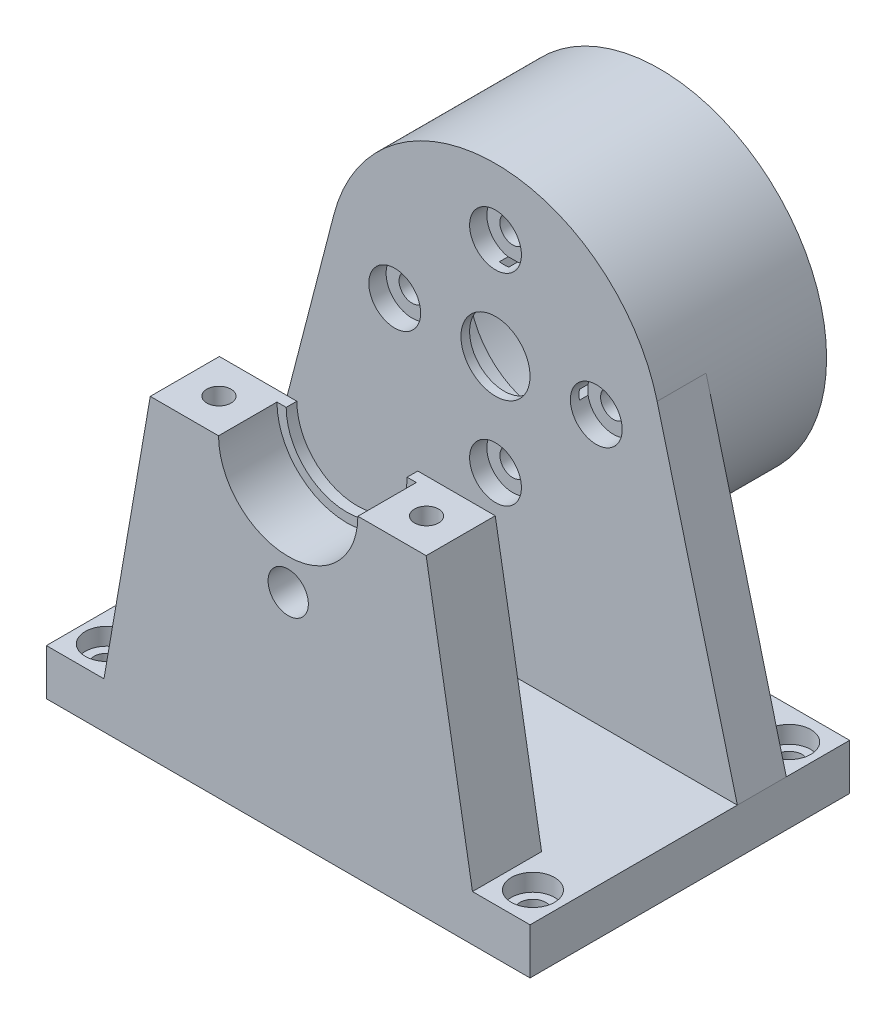
SolidWorks part; units mm, degrees
material "PET"
ref_plane "Piano frontale" through (0, 0, 0) normal (0, 0, 1) x (1, 0, 0)
ref_plane "Piano superiore" through (0, 0, 0) normal (0, 1, 0) x (1, 0, 0)
ref_plane "Piano destro" through (0, 0, 0) normal (1, 0, 0) x (0, 0, -1)
sketch "Schizzo1" plane through (0, 0, 0) normal (0, 0, 1) x (1, 0, 0)
  line L0 (-42, -54.5) -> (42, -54.5)
  line L1 (21, -17.1) -> (-21, -17.1)
  line L2 (21, -17.1) -> (21, 17.1)
  line L3 (21, 17.1) -> (-21, 17.1)
  line L4 (-21, -17.1) -> (-21, 17.1)
  line L5 (21, -17.1) -> (-21, 17.1) construction
  line L6 (21, 17.1) -> (-21, -17.1) construction
  line L7 (-42, -54.5) -> (-42, -46.5)
  line L8 (-42, -46.5) -> (-32, -46.5)
  line L9 (-32, -46.5) -> (-21, 17.1)
  line L10 (42, -54.5) -> (42, -46.5)
  line L11 (42, -46.5) -> (32, -46.5)
  line L12 (32, -46.5) -> (21, 17.1)
  line L13 (-23.9575, 0) -> (23.9575, 0)
  circle A0 centre (0, 0) radius 12.1
  point P9 (0, -54.5)
  dimension "D1" = 24.2
  dimension "D2" = 42
  dimension "D3" = 17.1
  dimension "D4" = 54.5
  dimension "D5" = 84
  dimension "D6" = 8
  dimension "D7" = 10
extrude "Estrusione-Estrusione1" add sketch "Schizzo1" along normal blind 12 contours A0 L13 L4 L1 L2 | L13 L9 L8 L7 L0 L10 L11 L12 L2 L1 L4
sketch "Schizzo2" plane through (0, 0, 12) normal (0, 0, 1) x (1, 0, 0)
  line L0 (-12.1, 0) -> (12.1, 0)
  circle A0 centre (0, 0) radius 10.5
  arc A1 (-12.1, 0) -> (12.1, 0) centre (0, 0) ccw construction
  arc A2 (-12.1, 0) -> (12.1, 0) centre (0, 0) ccw
  arc M11 (12.1, 0) -> (-12.1, 0) centre (0, 0) cw
  dimension "D1" = 21
extrude "Estrusione-Estrusione2" add sketch "Schizzo2" against normal blind 1.85 contours A0 L0 M11
sketch "Schizzo3" plane through (0, 0, 0) normal (0, 0, -1) x (-1, 0, 0)
  line L0 (-12.1, 0) -> (12.1, 0)
  circle A0 centre (0, 0) radius 10.5
  arc A1 (-12.1, 0) -> (12.1, 0) centre (0, 0) ccw construction
  arc A2 (-12.1, 0) -> (12.1, 0) centre (0, 0) ccw
  arc M3 (12.1, 0) -> (-12.1, 0) centre (0, 0) cw
  dimension "D1" = 21
extrude "Estrusione-Estrusione3" add sketch "Schizzo3" against normal blind 1.85 contours A0 L0 M3
sketch "Schizzo4" plane through (0, 0, 0) normal (0, 0, -1) x (-1, 0, 0)
  line L0 (-32, -46.5) -> (32, -46.5)
  line L9 (23.9575, 0) -> (10.5, 0)
  line L10 (-10.5, 0) -> (-23.9575, 0)
  line L11 (-23.9575, 0) -> (-32, -46.5)
  line L12 (-32, -46.5) -> (-42, -46.5)
  line L13 (-42, -46.5) -> (-42, -54.5)
  line L14 (-42, -54.5) -> (42, -54.5)
  line L15 (42, -54.5) -> (42, -46.5)
  line L16 (42, -46.5) -> (32, -46.5)
  line L17 (32, -46.5) -> (23.9575, 0)
  line L18 (23.9575, 0) -> (10.5, 0)
  line L19 (-10.5, 0) -> (-23.9575, 0)
  line L20 (-23.9575, 0) -> (-32, -46.5)
  line L21 (-32, -46.5) -> (-42, -46.5)
  line L22 (-42, -46.5) -> (-42, -54.5)
  line L23 (-42, -54.5) -> (42, -54.5)
  line L24 (42, -54.5) -> (42, -46.5)
  line L25 (42, -46.5) -> (32, -46.5)
  line L26 (32, -46.5) -> (23.9575, 0)
  circle A0 centre (0, 0) radius 54
  arc A1 (-10.5, 0) -> (10.5, 0) centre (0, 0) ccw
  arc A2 (-10.5, 0) -> (10.5, 0) centre (0, 0) ccw
  line M15 (-32, -46.5) -> (-42, -46.5)
  line M16 (-42, -46.5) -> (-42, -54.5)
  line M17 (-42, -54.5) -> (42, -54.5)
  line M18 (42, -54.5) -> (42, -46.5)
  line M19 (42, -46.5) -> (32, -46.5)
  dimension "D2" = 108
  dimension "D1" = 0
extrude "Estrusione-Estrusione4" add sketch "Schizzo4" along normal blind 23.5 contours A0 L0 M15 M16 M17 M18 M19
sketch "Schizzo5" plane through (0, 0, -23.5) normal (0, 0, -1) x (-1, 0, 0)
  line L9 (23.9575, 0) -> (10.5, 0)
  line L10 (32, -46.5) -> (23.9575, 0)
  line L11 (42, -46.5) -> (32, -46.5)
  line L12 (42, -54.5) -> (42, -46.5)
  line L13 (-42, -54.5) -> (42, -54.5)
  line L14 (-42, -46.5) -> (-42, -54.5)
  line L15 (-32, -46.5) -> (-42, -46.5)
  line L16 (-23.9575, 0) -> (-32, -46.5)
  line L17 (-10.5, 0) -> (-23.9575, 0)
  line L18 (23.9575, 0) -> (10.5, 0)
  line L19 (32, -46.5) -> (23.9575, 0)
  line L20 (42, -46.5) -> (32, -46.5)
  line L21 (42, -54.5) -> (42, -46.5)
  line L22 (-42, -54.5) -> (42, -54.5)
  line L23 (-42, -46.5) -> (-42, -54.5)
  line L24 (-32, -46.5) -> (-42, -46.5)
  line L25 (-23.9575, 0) -> (-32, -46.5)
  line L26 (-10.5, 0) -> (-23.9575, 0)
  arc A1 (-10.5, 0) -> (10.5, 0) centre (0, 0) ccw
  arc A2 (-10.5, 0) -> (10.5, 0) centre (0, 0) ccw
  dimension "D1" = 0
extrude "Estrusione-Estrusione5" add sketch "Schizzo5" along normal blind 1.85
sketch "Schizzo6" plane through (0, 0, -25.35) normal (0, 0, -1) x (-1, 0, 0)
  line L2 (-10.5, 0) -> (-12.1, 0)
  line L3 (12.1, 0) -> (10.5, 0)
  line L4 (-10.5, 0) -> (-12.1, 0)
  line L5 (12.1, 0) -> (10.5, 0)
  line L13 (-10.5, 0) -> (-23.9575, 0)
  line L14 (-23.9575, 0) -> (-32, -46.5)
  line L15 (-32, -46.5) -> (-42, -46.5)
  line L16 (-42, -46.5) -> (-42, -54.5)
  line L17 (-42, -54.5) -> (42, -54.5)
  line L18 (42, -54.5) -> (42, -46.5)
  line L19 (42, -46.5) -> (32, -46.5)
  line L20 (32, -46.5) -> (23.9575, 0)
  line L21 (23.9575, 0) -> (10.5, 0)
  line L22 (-10.5, 0) -> (-23.9575, 0)
  line L23 (-23.9575, 0) -> (-32, -46.5)
  line L24 (-32, -46.5) -> (-42, -46.5)
  line L25 (-42, -46.5) -> (-42, -54.5)
  line L26 (-42, -54.5) -> (42, -54.5)
  line L27 (42, -54.5) -> (42, -46.5)
  line L28 (42, -46.5) -> (32, -46.5)
  line L29 (32, -46.5) -> (23.9575, 0)
  line L30 (23.9575, 0) -> (10.5, 0)
  arc A1 (-10.5, 0) -> (10.5, 0) centre (0, 0) ccw
  arc A2 (-10.5, 0) -> (10.5, 0) centre (0, 0) ccw
  arc A3 (-12.1, 0) -> (12.1, 0) centre (0, 0) ccw
  arc A4 (-10.5, 0) -> (10.5, 0) centre (0, 0) ccw
  arc A5 (-12.1, 0) -> (12.1, 0) centre (0, 0) ccw
  arc A6 (-10.5, 0) -> (10.5, 0) centre (0, 0) ccw
  line M16 (-10.5, 0) -> (-23.9575, 0)
  line M17 (-23.9575, 0) -> (-32, -46.5)
  line M18 (-32, -46.5) -> (-42, -46.5)
  line M19 (-42, -46.5) -> (-42, -54.5)
  line M20 (-42, -54.5) -> (42, -54.5)
  line M21 (42, -54.5) -> (42, -46.5)
  line M22 (42, -46.5) -> (32, -46.5)
  line M23 (32, -46.5) -> (23.9575, 0)
  line M24 (23.9575, 0) -> (10.5, 0)
  dimension "D1" = 0
  dimension "D2" = 0
extrude "Estrusione-Estrusione6" add sketch "Schizzo6" along normal blind 8.3 contours A5 M16 M17 M18 M19 M20 M21 M22 M23 M24
sketch "Schizzo7" plane through (0, 0, -33.65) normal (0, 0, -1) x (-1, 0, 0)
  line L9 (23.9575, 0) -> (10.5, 0)
  line L10 (32, -46.5) -> (23.9575, 0)
  line L11 (42, -46.5) -> (32, -46.5)
  line L12 (42, -54.5) -> (42, -46.5)
  line L13 (-42, -54.5) -> (42, -54.5)
  line L14 (-42, -46.5) -> (-42, -54.5)
  line L15 (-32, -46.5) -> (-42, -46.5)
  line L16 (-23.9575, 0) -> (-32, -46.5)
  line L17 (-10.5, 0) -> (-23.9575, 0)
  line L18 (23.9575, 0) -> (10.5, 0)
  line L19 (32, -46.5) -> (23.9575, 0)
  line L20 (42, -46.5) -> (32, -46.5)
  line L21 (42, -54.5) -> (42, -46.5)
  line L22 (-42, -54.5) -> (42, -54.5)
  line L23 (-42, -46.5) -> (-42, -54.5)
  line L24 (-32, -46.5) -> (-42, -46.5)
  line L25 (-23.9575, 0) -> (-32, -46.5)
  line L26 (-10.5, 0) -> (-23.9575, 0)
  arc A1 (-10.5, 0) -> (10.5, 0) centre (0, 0) ccw
  arc A2 (-10.5, 0) -> (10.5, 0) centre (0, 0) ccw
  dimension "D1" = 0
extrude "Estrusione-Estrusione7" add sketch "Schizzo7" along normal blind 1.85
sketch "Schizzo8" plane through (0, 0, -35.5) normal (0, 0, -1) x (-1, 0, 0)
  line L0 (-32, -46.5) -> (32, -46.5)
  line L9 (-10.5, 0) -> (-23.9575, 0)
  line L10 (-23.9575, 0) -> (-32, -46.5)
  line L11 (-32, -46.5) -> (-42, -46.5)
  line L12 (-42, -46.5) -> (-42, -54.5)
  line L13 (-42, -54.5) -> (42, -54.5)
  line L14 (42, -54.5) -> (42, -46.5)
  line L15 (42, -46.5) -> (32, -46.5)
  line L16 (32, -46.5) -> (23.9575, 0)
  line L17 (23.9575, 0) -> (10.5, 0)
  line L18 (-10.5, 0) -> (-23.9575, 0)
  line L19 (-23.9575, 0) -> (-32, -46.5)
  line L20 (-32, -46.5) -> (-42, -46.5)
  line L21 (-42, -46.5) -> (-42, -54.5)
  line L22 (-42, -54.5) -> (42, -54.5)
  line L23 (42, -54.5) -> (42, -46.5)
  line L24 (42, -46.5) -> (32, -46.5)
  line L25 (32, -46.5) -> (23.9575, 0)
  line L26 (23.9575, 0) -> (10.5, 0)
  arc A1 (-10.5, 0) -> (10.5, 0) centre (0, 0) ccw
  arc A2 (-10.5, 0) -> (10.5, 0) centre (0, 0) ccw
  line M14 (-32, -46.5) -> (-42, -46.5)
  line M15 (-42, -46.5) -> (-42, -54.5)
  line M16 (-42, -54.5) -> (42, -54.5)
  line M17 (42, -54.5) -> (42, -46.5)
  line M18 (42, -46.5) -> (32, -46.5)
  dimension "D1" = 0
extrude "Estrusione-Estrusione8" add sketch "Schizzo8" along normal blind 23.5 contours L0 M14 M15 M16 M17 M18
sketch "Schizzo9" plane through (0, 0, -59) normal (0, 0, -1) x (-1, 0, 0)
  line L9 (23.9575, 0) -> (10.5, 0)
  line L10 (32, -46.5) -> (23.9575, 0)
  line L11 (42, -46.5) -> (32, -46.5)
  line L12 (42, -54.5) -> (42, -46.5)
  line L13 (-42, -54.5) -> (42, -54.5)
  line L14 (-42, -46.5) -> (-42, -54.5)
  line L15 (-32, -46.5) -> (-42, -46.5)
  line L16 (-23.9575, 0) -> (-32, -46.5)
  line L17 (-10.5, 0) -> (-23.9575, 0)
  line L18 (23.9575, 0) -> (10.5, 0)
  line L19 (32, -46.5) -> (23.9575, 0)
  line L20 (42, -46.5) -> (32, -46.5)
  line L21 (42, -54.5) -> (42, -46.5)
  line L22 (-42, -54.5) -> (42, -54.5)
  line L23 (-42, -46.5) -> (-42, -54.5)
  line L24 (-32, -46.5) -> (-42, -46.5)
  line L25 (-23.9575, 0) -> (-32, -46.5)
  line L26 (-10.5, 0) -> (-23.9575, 0)
  arc A1 (-10.5, 0) -> (10.5, 0) centre (0, 0) ccw
  arc A2 (-10.5, 0) -> (10.5, 0) centre (0, 0) ccw
  dimension "D1" = 0
extrude "Estrusione-Estrusione9" add sketch "Schizzo9" along normal blind 1.85
sketch "Schizzo10" plane through (0, 0, -60.85) normal (0, 0, -1) x (-1, 0, 0)
  line L0 (-10.5, 0) -> (-23.9575, 0) construction
  line L1 (-23.9575, 0) -> (-32, -46.5) construction
  line L2 (-32, -46.5) -> (-42, -46.5) construction
  line L3 (-42, -46.5) -> (-42, -54.5) construction
  line L4 (-42, -54.5) -> (42, -54.5) construction
  line L5 (42, -54.5) -> (42, -46.5) construction
  line L6 (42, -46.5) -> (32, -46.5) construction
  line L7 (32, -46.5) -> (23.9575, 0) construction
  line L8 (23.9575, 0) -> (10.5, 0) construction
  line L9 (-10.5, 0) -> (-12.1, 0) construction
  line L10 (12.1, 0) -> (10.5, 0) construction
  line L11 (-10.5, 0) -> (-23.9575, 0)
  line L12 (-23.9575, 0) -> (-32, -46.5)
  line L13 (-32, -46.5) -> (-42, -46.5)
  line L14 (-42, -46.5) -> (-42, -54.5)
  line L15 (-42, -54.5) -> (42, -54.5)
  line L16 (42, -54.5) -> (42, -46.5)
  line L17 (42, -46.5) -> (32, -46.5)
  line L18 (32, -46.5) -> (23.9575, 0)
  line L19 (23.9575, 0) -> (10.5, 0)
  line L20 (-10.5, 0) -> (-12.1, 0)
  line L21 (12.1, 0) -> (10.5, 0)
  arc A0 (-10.5, 0) -> (10.5, 0) centre (0, 0) ccw construction
  arc A1 (-12.1, 0) -> (12.1, 0) centre (0, 0) ccw construction
  arc A2 (-10.5, 0) -> (10.5, 0) centre (0, 0) ccw construction
  arc A3 (-10.5, 0) -> (10.5, 0) centre (0, 0) ccw
  arc A4 (-12.1, 0) -> (12.1, 0) centre (0, 0) ccw
  arc A5 (-10.5, 0) -> (10.5, 0) centre (0, 0) ccw
  line M3 (-23.9575, 0) -> (-32, -46.5)
  line M4 (-32, -46.5) -> (-42, -46.5)
  line M5 (-42, -46.5) -> (-42, -54.5)
  line M6 (-42, -54.5) -> (42, -54.5)
  line M7 (42, -54.5) -> (42, -46.5)
  line M8 (42, -46.5) -> (32, -46.5)
  line M9 (32, -46.5) -> (23.9575, 0)
  line M10 (23.9575, 0) -> (10.5, 0)
extrude "Estrusione-Estrusione10" add sketch "Schizzo10" along normal blind 8.3 contours A4 L11 M3 M4 M5 M6 M7 M8 M9 M10
sketch "Schizzo11" plane through (0, 0, -69.15) normal (0, 0, -1) x (-1, 0, 0)
  line L9 (23.9575, 0) -> (10.5, 0)
  line L10 (32, -46.5) -> (23.9575, 0)
  line L11 (42, -46.5) -> (32, -46.5)
  line L12 (42, -54.5) -> (42, -46.5)
  line L13 (-42, -54.5) -> (42, -54.5)
  line L14 (-42, -46.5) -> (-42, -54.5)
  line L15 (-32, -46.5) -> (-42, -46.5)
  line L16 (-23.9575, 0) -> (-32, -46.5)
  line L17 (-10.5, 0) -> (-23.9575, 0)
  line L18 (23.9575, 0) -> (10.5, 0)
  line L19 (32, -46.5) -> (23.9575, 0)
  line L20 (42, -46.5) -> (32, -46.5)
  line L21 (42, -54.5) -> (42, -46.5)
  line L22 (-42, -54.5) -> (42, -54.5)
  line L23 (-42, -46.5) -> (-42, -54.5)
  line L24 (-32, -46.5) -> (-42, -46.5)
  line L25 (-23.9575, 0) -> (-32, -46.5)
  line L26 (-10.5, 0) -> (-23.9575, 0)
  arc A1 (-10.5, 0) -> (10.5, 0) centre (0, 0) ccw
  arc A2 (-10.5, 0) -> (10.5, 0) centre (0, 0) ccw
  dimension "D1" = 0
extrude "Estrusione-Estrusione11" add sketch "Schizzo11" along normal blind 1.85 contours L18 A2 L26 L25 L24 L23 L22 L21 L20 L19
sketch "Schizzo12" plane through (0, -46.5, 0) normal (0, 1, 0) x (1, 0, 0)
  line L0 (37, -12) -> (37, 71) construction
  line L1 (42, -12) -> (32, -12) construction
  line L2 (32, 71) -> (42, 71) construction
  line L3 (-37, -12) -> (-37, 71) construction
  line L4 (-42, -12) -> (-32, -12) construction
  line L5 (-42, 71) -> (-32, 71) construction
  circle A0 centre (37, -6.5) radius 2.25
  circle A1 centre (37, 28.5) radius 2.25
  circle A2 centre (37, 65.5) radius 2.25
  circle A3 centre (-37, -6.5) radius 2.25
  circle A4 centre (-37, 28.5) radius 2.25
  circle A5 centre (-37, 65.5) radius 2.25
  dimension "D1" = 4.5
  dimension "D2" = 5.5
  dimension "D3" = 5.5
  dimension "D4" = 40.5
  dimension "D5" = 40.5
  dimension "D6" = 77.5
  dimension "D7" = 77.5
extrude "Taglio-Estrusione1" cut sketch "Schizzo12" against normal through all
sketch "Schizzo13" plane through (0, 0, 0) normal (0, 1, 0) x (1, 0, 0)
  line L0 (12.1, 29.5) -> (23.9575, 29.5) construction
  line L1 (12.1, 33.65) -> (12.1, 25.35) construction
  line L2 (23.9575, 35.5) -> (23.9575, 23.5) construction
  line L3 (-12.1, 29.5) -> (-23.9575, 29.5) construction
  line L4 (-12.1, 33.65) -> (-12.1, 25.35) construction
  line L5 (-23.9575, 35.5) -> (-23.9575, 23.5) construction
  line L6 (23.9575, 65) -> (12.1, 65) construction
  line L7 (23.9575, 71) -> (23.9575, 59) construction
  line L8 (12.1, 69.15) -> (12.1, 60.85) construction
  line L9 (-12.1, 65) -> (-23.9575, 65) construction
  line L10 (-12.1, 69.15) -> (-12.1, 60.85) construction
  line L11 (-23.9575, 71) -> (-23.9575, 59) construction
  line L12 (23.9575, -6) -> (12.1, -6) construction
  line L13 (23.9575, -12) -> (23.9575, 0) construction
  line L14 (12.1, -10.15) -> (12.1, -1.85) construction
  line L15 (-12.1, -6) -> (-23.9575, -6) construction
  line L16 (-12.1, -10.15) -> (-12.1, -1.85) construction
  line L17 (-23.9575, -12) -> (-23.9575, 0) construction
  circle A0 centre (18.0288, -6) radius 2.1
  circle A1 centre (-18.0288, -6) radius 2.1
  circle A2 centre (18.0288, 29.5) radius 2.1
  circle A3 centre (-18.0288, 29.5) radius 2.1
  circle A4 centre (18.0288, 65) radius 2.1
  circle A5 centre (-18.0288, 65) radius 2.1
  dimension "D1" = 4.2
extrude "Taglio-Estrusione2" cut sketch "Schizzo13" against normal blind 6
sketch "Schizzo15" plane through (0, -6, 0) normal (0, 1, 0) x (1, 0, 0)
  circle A0 centre (-18.0288, 65) radius 2.1 construction
  circle A1 centre (18.0288, 65) radius 2.1 construction
  circle A2 centre (18.0288, 29.5) radius 2.1 construction
  circle A3 centre (-18.0288, 29.5) radius 2.1 construction
  circle A4 centre (-18.0288, -6) radius 2.1 construction
  circle A5 centre (18.0288, -6) radius 2.1 construction
  circle A6 centre (-18.0288, 65) radius 2.1
  circle A7 centre (18.0288, 65) radius 2.1
  circle A8 centre (18.0288, 29.5) radius 2.1
  circle A9 centre (-18.0288, 29.5) radius 2.1
  circle A10 centre (-18.0288, -6) radius 2.1
  circle A11 centre (18.0288, -6) radius 2.1
extrude "Taglio-Estrusione4" cut sketch "Schizzo15" against normal blind 5
sketch "Schizzo16" plane through (0, -54.5, 0) normal (0, -1, 0) x (1, 0, 0)
  line L0 (-23.9575, 0) -> (-10.5, 0) construction
  line L1 (10.5, 0) -> (23.9575, 0) construction
  line L2 (-23.9575, 0) -> (-10.5, 0)
  line L3 (10.5, 0) -> (23.9575, 0)
  line L4 (-10.5, 0) -> (10.5, 0)
  line L5 (-10.5, 1.85) -> (-10.5, 0)
  line L6 (10.5, 1.85) -> (-10.5, 1.85)
  line L7 (10.5, 0) -> (10.5, 1.85)
  line L8 (-10.5, 0) -> (10.5, 0)
  line L9 (-10.5, 1.85) -> (-10.5, 0)
  line L10 (10.5, 1.85) -> (-10.5, 1.85)
  line L11 (10.5, 0) -> (10.5, 1.85)
  line L12 (42, 12) -> (42, -71) construction
  line L13 (42, 0) -> (-42, 0)
  line L14 (42, 0) -> (42, -71)
  line L15 (42, -71) -> (-42, -71)
  line L16 (-42, 0) -> (-42, -71)
  line L17 (42, -71) -> (-42, -71) construction
  line L18 (-42, 12) -> (-42, -71) construction
  circle M5 centre (37, -28.5) radius 2.25
  circle M6 centre (37, -65.5) radius 2.25
  circle M8 centre (-37, -28.5) radius 2.25
  circle M9 centre (-37, -65.5) radius 2.25
  line M11 (-42, 12) -> (-42, -71)
  line M12 (-42, -71) -> (42, -71)
  line M13 (42, -71) -> (42, 12)
  dimension "D1" = 0
extrude "Taglio-Estrusione5" cut sketch "Schizzo16" against normal through all contours L13 L3 L8 L2 M13 M11 M12 M5 M9 M8 M6
sketch "Schizzo17" plane through (0, 0, 0) normal (0, 0, -1) x (-1, 0, 0)
  line L0 (-32, -46.5) -> (32, -46.5)
  line L9 (42, -46.5) -> (32, -46.5)
  line L10 (32, -46.5) -> (23.9575, 0)
  line L11 (23.9575, 0) -> (10.5, 0)
  line L12 (-10.5, 0) -> (-23.9575, 0)
  line L13 (-23.9575, 0) -> (-32, -46.5)
  line L14 (-32, -46.5) -> (-42, -46.5)
  line L15 (-42, -46.5) -> (-42, -54.5)
  line L16 (-42, -54.5) -> (42, -54.5)
  line L17 (42, -54.5) -> (42, -46.5)
  line L18 (42, -46.5) -> (32, -46.5)
  line L19 (32, -46.5) -> (23.9575, 0)
  line L20 (23.9575, 0) -> (10.5, 0)
  line L21 (-10.5, 0) -> (-23.9575, 0)
  line L22 (-23.9575, 0) -> (-32, -46.5)
  line L23 (-32, -46.5) -> (-42, -46.5)
  line L24 (-42, -46.5) -> (-42, -54.5)
  line L25 (-42, -54.5) -> (42, -54.5)
  line L26 (42, -54.5) -> (42, -46.5)
  arc A1 (-10.5, 0) -> (10.5, 0) centre (0, 0) ccw
  arc A2 (-10.5, 0) -> (10.5, 0) centre (0, 0) ccw
  line M11 (42, -46.5) -> (32, -46.5)
  line M17 (-32, -46.5) -> (-42, -46.5)
  line M18 (-42, -46.5) -> (-42, -54.5)
  line M19 (-42, -54.5) -> (42, -54.5)
  line M20 (42, -54.5) -> (42, -46.5)
  dimension "D1" = 0
extrude "Estrusione-Estrusione12" add sketch "Schizzo17" along normal blind 24 contours L0 M17 M18 M19 M20 M11
sketch "Schizzo18" plane through (0, 0, -24) normal (0, 0, -1) x (-1, 0, 0)
  line L0 (-42, -46.5) -> (-28.0737, 7.2709)
  line L1 (42, -46.5) -> (28.0737, 7.2709)
  line L4 (42, -46.5) -> (-42, -46.5)
  line L5 (-42, -46.5) -> (-42, -54.5)
  line L6 (-42, -54.5) -> (42, -54.5)
  line L7 (42, -54.5) -> (42, -46.5)
  line L9 (-42, -46.5) -> (-42, -54.5)
  line L10 (-42, -54.5) -> (42, -54.5)
  line L11 (42, -54.5) -> (42, -46.5)
  arc A0 (28.0737, 7.2709) -> (-28.0737, 7.2709) centre (0, 0) ccw
  circle A1 centre (0, 0) radius 6
  circle A2 centre (0, 0) radius 17.5 construction
  circle A3 centre (0, 17.5) radius 2.25
  circle A4 centre (17.5, 0) radius 2.25
  circle A5 centre (0, -17.5) radius 2.25
  circle A6 centre (-17.5, 0) radius 2.25
  dimension "D1" = 58
  dimension "D2" = 12
  dimension "D3" = 35
  dimension "D4" = 4.5
  dimension "D5" = 0
extrude "Estrusione-Estrusione13" add sketch "Schizzo18" along normal blind 8.5
sketch "Schizzo19" plane through (0, 0, -32.5) normal (0, 0, -1) x (-1, 0, 0)
  circle A0 centre (0, 0) radius 13.1
  dimension "D1" = 26.2
extrude "Taglio-Estrusione6" cut sketch "Schizzo19" against normal blind 7
sketch "Schizzo20" plane through (0, 0, -32.5) normal (0, 0, -1) x (-1, 0, 0)
  circle A0 centre (0, 0) radius 26.25
  circle A1 centre (0, 0) radius 29
  dimension "D1" = 52.5
extrude "Estrusione-Estrusione14" add sketch "Schizzo20" along normal blind 20
sketch "Schizzo21" plane through (0, 0, 12) normal (0, 0, 1) x (1, 0, 0)
  circle A0 centre (0, -17.5) radius 2.25 construction
  circle A1 centre (0, -17.5) radius 2.25
  circle A2 centre (0, -17.5) radius 3.5
  dimension "D1" = 7
extrude "Taglio-Estrusione8" cut sketch "Schizzo21" against normal up to next contours A1 | A2 A1
sketch "Schizzo22" plane through (0, 0, -32.5) normal (0, 0, -1) x (-1, 0, 0)
  line L1 (-42, -46.5) -> (42, -46.5)
  line L2 (-42, -46.5) -> (-42, -54.5)
  line L3 (-42, -54.5) -> (42, -54.5)
  line L4 (42, -46.5) -> (42, -54.5)
extrude "Estrusione-Estrusione15" add sketch "Schizzo22" along normal blind 11
sketch "Schizzo23" plane through (0, -46.5, 0) normal (0, 1, 0) x (1, 0, 0)
  line L0 (37, -12) -> (37, 43.5) construction
  line L1 (42, -12) -> (32, -12) construction
  line L2 (-42, 43.5) -> (42, 43.5) construction
  line L3 (-37, -12) -> (-37, 43.5) construction
  line L4 (-42, -12) -> (-32, -12) construction
  circle A0 centre (37, 38) radius 2.25
  circle A1 centre (-37, 38) radius 2.25
  dimension "D3" = 4.5
  dimension "D1" = 5.5
  dimension "D2" = 5.5
extrude "Taglio-Estrusione9" cut sketch "Schizzo23" against normal through all
sketch "Schizzo24" plane through (0, -46.5, 0) normal (0, 1, 0) x (1, 0, 0)
  circle A0 centre (37, -6.5) radius 3.75
  circle A1 centre (-37, -6.5) radius 3.75
  circle A2 centre (-37, 38) radius 3.75
  circle A3 centre (37, 38) radius 3.75
  dimension "D1" = 7.5
extrude "Taglio-Estrusione10" cut sketch "Schizzo24" against normal blind 3
sketch "Schizzo25" plane through (0, 0, 10.15) normal (0, 0, -1) x (-1, 0, 0)
  line L2 (-10.5, 0) -> (-12.1, 0)
  line L3 (12.1, 0) -> (10.5, 0)
  line L4 (-10.5, 0) -> (-12.1, 0)
  line L5 (12.1, 0) -> (10.5, 0)
  arc A2 (-10.5, 0) -> (10.5, 0) centre (0, 0) ccw
  arc A3 (-12.1, 0) -> (12.1, 0) centre (0, 0) ccw
  arc A4 (-10.5, 0) -> (10.5, 0) centre (0, 0) ccw
  arc A5 (-12.1, 0) -> (12.1, 0) centre (0, 0) ccw
  dimension "D1" = 0
extrude "Taglio-Estrusione11" cut sketch "Schizzo25" against normal through all
sketch "Schizzo26" plane through (0, 0, -24) normal (0, 0, 1) x (1, 0, 0)
  circle A0 centre (0, 17.5) radius 4.5
  circle A1 centre (17.5, 0) radius 4.5
  circle A2 centre (0, -17.5) radius 4.5
  circle A3 centre (-17.5, 0) radius 4.5
  dimension "D1" = 9
extrude "Taglio-Estrusione12" cut sketch "Schizzo26" against normal blind 3
